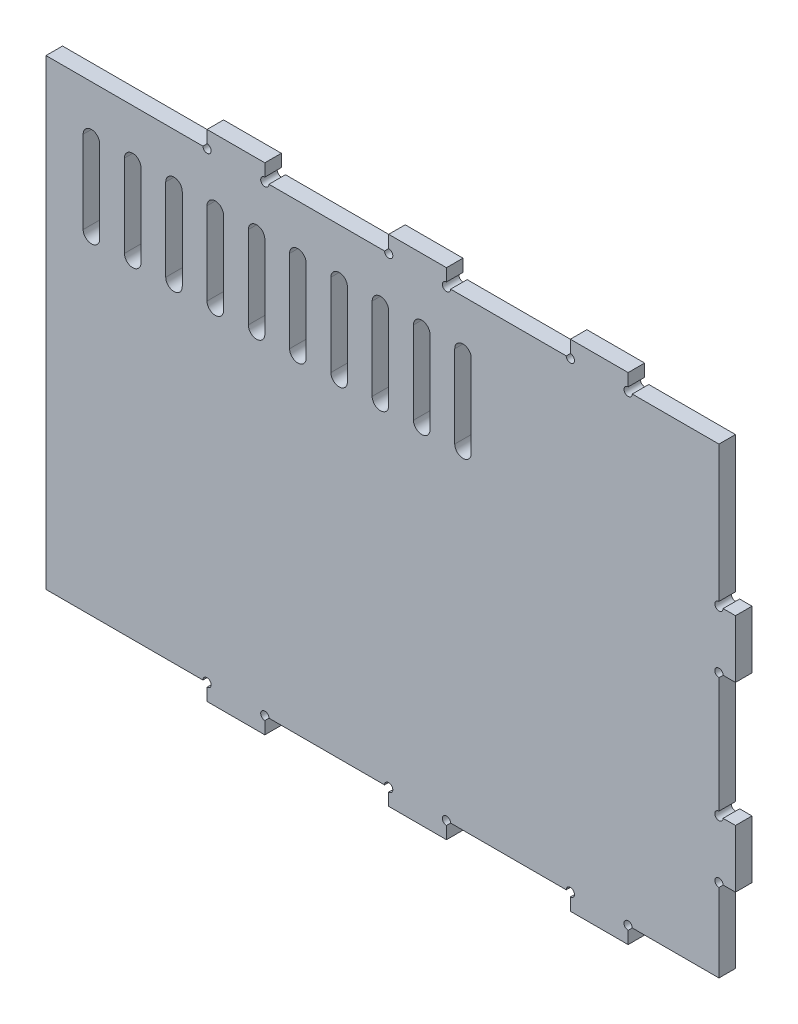
SolidWorks part; units mm, degrees
ref_plane "Front" through (0, 0, 0) normal (0, 0, 1) x (1, 0, 0)
ref_plane "Top" through (0, 0, 0) normal (0, 1, 0) x (1, 0, 0)
ref_plane "Right" through (0, 0, 0) normal (1, 0, 0) x (0, 0, -1)
sketch "草图1" plane through (0, 0, 0) normal (0, 0, 1) x (1, 0, 0)
  line L1 (0, 0) -> (95, 0)
  line L2 (0, 0) -> (0, 56)
  line L3 (0, 56) -> (95, 56)
  line L4 (95, 0) -> (95, 56)
  dimension "D1" = 56
  dimension "D2" = 95
extrude "凸台-拉伸1" add sketch "草图1" along normal blind 2
sketch "草图2" plane through (0, 0, 0) normal (0, 0, -1) x (-1, 0, 0)
  line L0 (-95, 0) -> (-95, 56) construction
  line L1 (-90, 51) -> (-70, 51)
  line L2 (-90, 51) -> (-90, 39)
  line L3 (-90, 39) -> (-70, 39)
  line L4 (-70, 51) -> (-70, 39)
  line L5 (-95, 56) -> (0, 56) construction
  dimension "D1" = 12
  dimension "D2" = 20
  dimension "D3" = 5
  dimension "D4" = 5
sketch "草图3" plane through (0, 0, 0) normal (0, 0, -1) x (-1, 0, 0)
  line L0 (0, 0) -> (-95, 0) construction
  line L1 (0, 56) -> (-13.5, 56)
  line L2 (0, 56) -> (0, 0)
  line L3 (0, 0) -> (-13.5, 0)
  line L4 (-13.5, 56) -> (-13.5, 0)
  dimension "D1" = 13.5
extrude "切除-拉伸2" cut sketch "草图3" against normal through all
sketch "草图6" plane through (0, 0, 0) normal (0, 0, -1) x (-1, 0, 0)
  line L0 (-64, 50) -> (-64, 40) construction
  line L1 (-63, 50) -> (-63, 40)
  line L2 (-65, 50) -> (-65, 40)
  line L3 (-95, 0) -> (-95, 56) construction
  line L4 (-95, 56) -> (-13.5, 56) construction
  arc A0 (-63, 50) -> (-65, 50) centre (-64, 50) ccw
  arc A1 (-65, 40) -> (-63, 40) centre (-64, 40) ccw
  point P2 (-64, 45)
  dimension "D4" = 6
  dimension "D1" = 2
  dimension "D2" = 10
  dimension "D3" = 30
extrude "切除-拉伸4" cut sketch "草图6" against normal through all
pattern_linear "阵列(线性)1" count 10 spacing 5 along (-1, 0, 0) of "切除-拉伸4"
sketch "草图10" plane through (0, 0, 0) normal (0, 0, -1) x (-1, 0, 0)
  line L0 (-95, 56) -> (-13.5, 56) construction
  line L6 (-95, 0) -> (-95, 56) construction
  line L7 (-40, 56) -> (-33, 56)
  line L8 (-40, 56) -> (-40, 58)
  line L9 (-40, 58) -> (-33, 58)
  line L10 (-33, 56) -> (-33, 58)
  line L11 (-84, 56) -> (-77, 56)
  line L12 (-84, 56) -> (-84, 58)
  line L13 (-84, 58) -> (-77, 58)
  line L14 (-77, 56) -> (-77, 58)
  line L15 (-62, 56) -> (-55, 56)
  line L16 (-62, 56) -> (-62, 58)
  line L17 (-62, 58) -> (-55, 58)
  line L18 (-55, 56) -> (-55, 58)
  line L19 (-13.5, 0) -> (-95, 0) construction
  line L20 (-84, 0) -> (-77, 0)
  line L21 (-84, 0) -> (-84, -2)
  line L22 (-84, -2) -> (-77, -2)
  line L23 (-77, 0) -> (-77, -2)
  line L24 (-95, 0) -> (-95, 56) construction
  line L26 (-62, 0) -> (-55, 0)
  line L27 (-62, 0) -> (-62, -2)
  line L28 (-62, -2) -> (-55, -2)
  line L29 (-55, 0) -> (-55, -2)
  line L30 (-40, 0) -> (-33, 0)
  line L31 (-40, 0) -> (-40, -2)
  line L32 (-40, -2) -> (-33, -2)
  line L33 (-33, 0) -> (-33, -2)
  dimension "D2" = 7
  dimension "D3" = 2
  dimension "D4" = 2
  dimension "D5" = 7
  dimension "D6" = 15
  dimension "D7" = 2
  dimension "D8" = 7
  dimension "D9" = 2
  dimension "D10" = 7
  dimension "D11" = 11
  dimension "D12" = 15
  dimension "D13" = 11
  dimension "D14" = 2
  dimension "D15" = 7
  dimension "D16" = 15
  dimension "D17" = 2
  dimension "D18" = 7
  dimension "D19" = 15
extrude "凸台-拉伸2" add sketch "草图10" against normal blind 2
sketch "草图11" plane through (0, 0, 0) normal (0, 0, -1) x (-1, 0, 0)
  circle A0 centre (-84, 56) radius 0.5
  circle A1 centre (-77, 56) radius 0.5
  circle A2 centre (-62, 56) radius 0.5
  circle A3 centre (-55, 56) radius 0.5
  circle A4 centre (-40, 56) radius 0.5
  circle A5 centre (-33, 56) radius 0.5
  circle A6 centre (-84, 0) radius 0.5
  circle A7 centre (-77, 0) radius 0.5
  circle A8 centre (-62, 0) radius 0.5
  circle A9 centre (-55, 0) radius 0.5
  circle A10 centre (-40, 0) radius 0.5
  circle A11 centre (-33, 0) radius 0.5
extrude "切除-拉伸7" cut sketch "草图11" against normal through all
sketch "草图13" plane through (0, 0, 0) normal (0, 0, -1) x (-1, 0, 0)
  line L0 (-95, 0) -> (-95, 56) construction
  line L1 (-95, 10) -> (-97, 10)
  line L2 (-95, 10) -> (-95, 17)
  line L3 (-95, 17) -> (-97, 17)
  line L4 (-97, 10) -> (-97, 17)
  line L5 (-84.5, 0) -> (-95, 0) construction
  line L7 (-95, 32) -> (-97, 32)
  line L8 (-95, 32) -> (-95, 39)
  line L9 (-95, 39) -> (-97, 39)
  line L10 (-97, 32) -> (-97, 39)
  dimension "D1" = 2
  dimension "D2" = 7
  dimension "D3" = 10
  dimension "D4" = 2
  dimension "D5" = 7
  dimension "D6" = 15
extrude "凸台-拉伸4" add sketch "草图13" against normal blind 2
sketch "草图14" plane through (0, 0, 0) normal (0, 0, -1) x (-1, 0, 0)
  circle A0 centre (-95, 39) radius 0.5
  circle A1 centre (-95, 32) radius 0.5
  circle A2 centre (-95, 17) radius 0.5
  circle A3 centre (-95, 10) radius 0.5
extrude "切除-拉伸8" cut sketch "草图14" against normal through all
